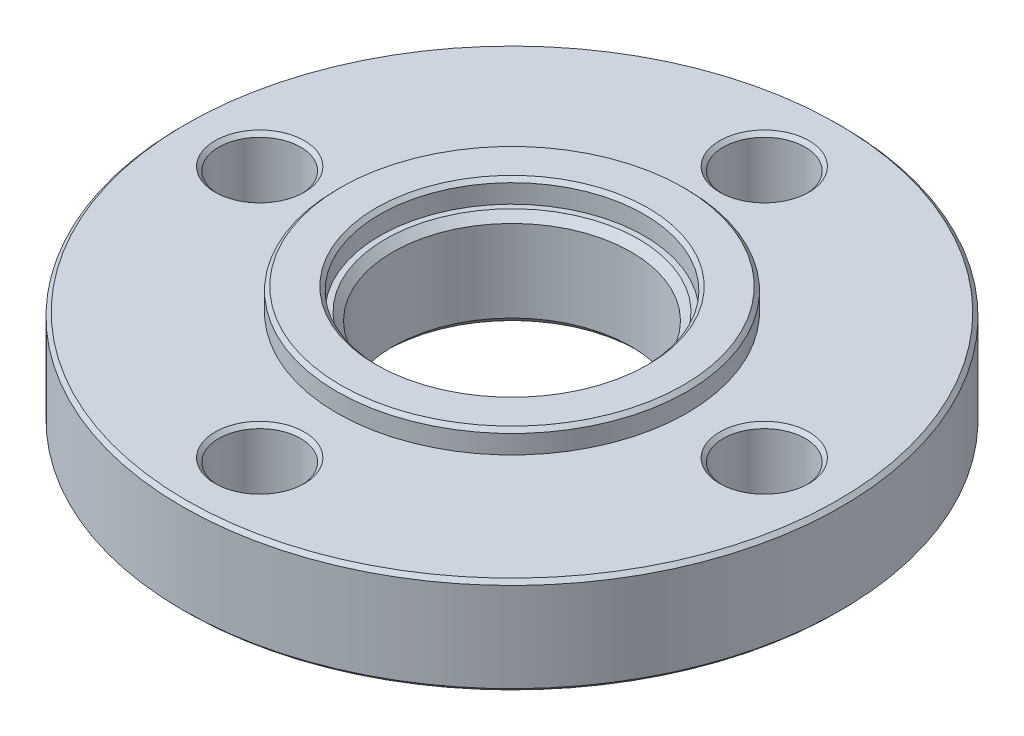
SolidWorks part; units mm, degrees
ref_plane "Alzado" through (0, 0, 0) normal (0, 0, 1) x (1, 0, 0)
ref_plane "Planta" through (0, 0, 0) normal (0, 1, 0) x (1, 0, 0)
ref_plane "Vista lateral" through (0, 0, 0) normal (1, 0, 0) x (0, 0, -1)
sketch "Croquis1" plane through (0, 0, 0) normal (1, 0, 0) x (0, 0, -1)
  line L0 (-16, -6.5) -> (-16, 6.5)
  line L1 (-16, 6.5) -> (-17.75, 6.5)
  line L2 (-17.75, 6.5) -> (-17.75, 9.5)
  line L3 (-17.75, 9.5) -> (-23.5, 9.5)
  line L4 (-23.5, 9.5) -> (-23.5, 6.5)
  line L5 (-23.5, 6.5) -> (-44.25, 6.5)
  line L6 (-44.25, 6.5) -> (-44.25, -6.5)
  line L7 (-44.25, -6.5) -> (-16, -6.5)
  line L8 (0, 0) -> (0, -50131.2274) construction
  point P10 (-16, 0)
  dimension "D1" = 16
  dimension "D2" = 23.5
  dimension "D3" = 17.75
  dimension "D4" = 44.25
  dimension "D5" = 3
  dimension "D6" = 13
revolve "Revolución1" add sketch "Croquis1" angle 360 about L8
sketch "Croquis2" plane through (0, 0, 0) normal (0, 1, 0) x (1, 0, 0)
  line L0 (0, 23.5) -> (0, 44.25) construction
  circle A0 centre (0, 33.875) radius 5.5
  circle A1 centre (33.875, 0) radius 5.5
  circle A2 centre (0, -33.875) radius 5.5
  circle A3 centre (-33.875, 0) radius 5.5
  circle A4 centre (0, 0) radius 23.5 construction
  circle A5 centre (0, 0) radius 23.5 construction
  circle A6 centre (0, 0) radius 44.25 construction
  point P10 (0, 0)
  point P19 (0, 33.875)
  dimension "D1" = 11
  dimension "D2" = 4
extrude "Cortar-Extruir1" cut sketch "Croquis2" against normal through all both and the other way through all
chamfer "Chaflán1" distance 1 angle 45 2 edges at (0, -6.5, 16) (0, 6.5, 16)
chamfer "Chaflán2" distance 0.5 angle 45 12 edges at (0, 9.5, 17.75) (0, 9.5, 23.5) (0, 6.5, 44.25) (0, -6.5, 44.25) (33.875, -6.5, 5.5) (33.875, 6.5, 5.5) (0, -6.5, -28.375) (0, 6.5, -28.375) (-33.875, -6.5, 5.5) (-33.875, 6.5, 5.5) (0, -6.5, 39.375) (0, 6.5, 39.375)
